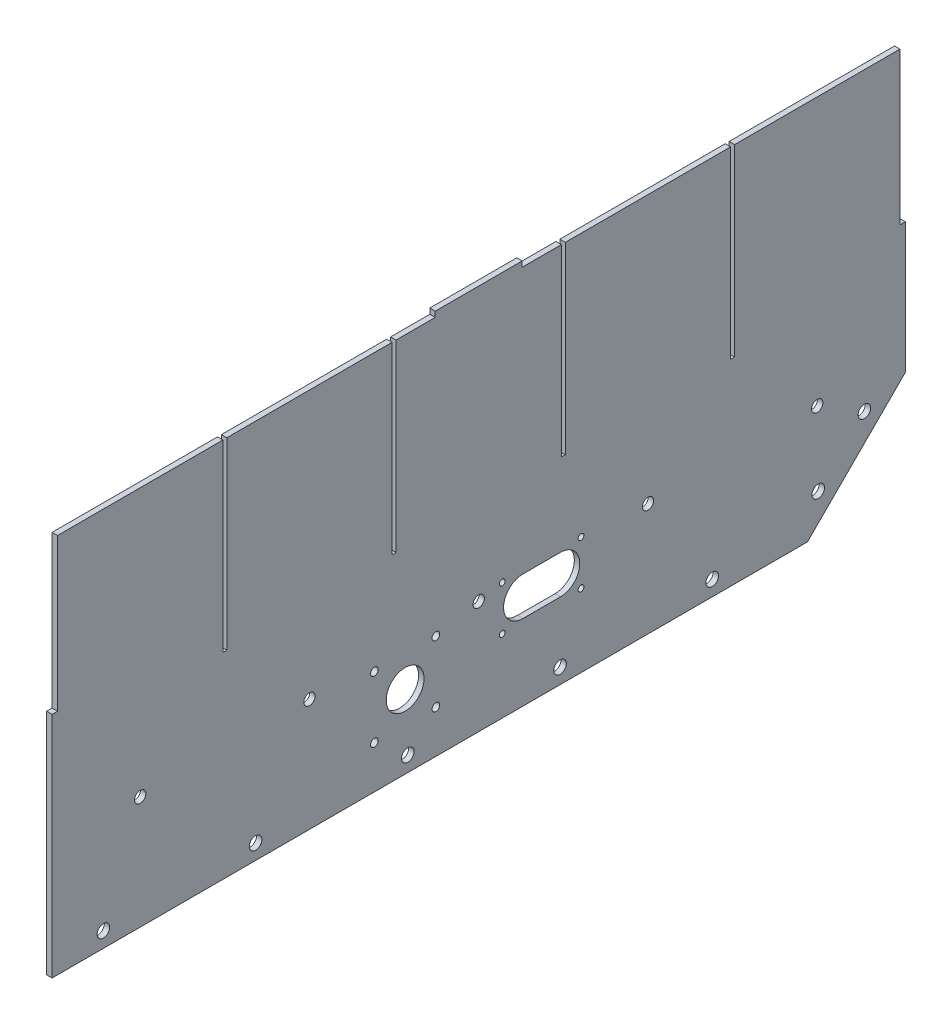
SolidWorks part; units mm, degrees
material "6061-T6 (SS)"
ref_plane "X-Y Datum" through (0, 0, 0) normal (0, 0, 1) x (1, 0, 0)
ref_plane "X-Z Datum" through (0, 0, 0) normal (0, 1, 0) x (1, 0, 0)
ref_plane "Y-Z Datum" through (0, 0, 0) normal (1, 0, 0) x (0, 0, -1)
sketch "Sketch1" plane through (0, 0, 0) normal (1, 0, 0) x (0, 0, -1)
  line L1 (-249.174, 82.55) -> (249.174, 82.55)
  line L2 (-249.174, 82.55) -> (-249.174, -82.55)
  line L3 (-249.174, -82.55) -> (249.174, -82.55)
  line L4 (249.174, 82.55) -> (249.174, -82.55)
  line L5 (-249.174, 82.55) -> (249.174, -82.55) construction
  line L6 (-249.174, -82.55) -> (249.174, 82.55) construction
  point P0 (0, 0)
  dimension "D1" = 165.1
  dimension "D2" = 498.348
extrude "Boss-Extrude1" add sketch "Sketch1" along normal mid plane 3.175
sketch "Sketch2" plane through (1.5875, 0, 0) normal (1, 0, 0) x (0, 0, -1)
  line L2 (249.174, -82.55) -> (192.024, -139.7)
  line L5 (-249.174, -82.55) -> (249.174, -82.55) construction
  line L6 (-249.174, -82.55) -> (249.174, -82.55)
  line L8 (192.024, -139.7) -> (-249.174, -139.7)
  line L9 (-249.174, -139.7) -> (-249.174, -82.55)
  line L11 (-249.174, 82.55) -> (-249.174, -82.55) construction
  line L12 (249.174, -82.55) -> (249.174, 82.55) construction
  dimension "D1" = 45
  dimension "D5" = 57.15
extrude "Boss-Extrude2" add sketch "Sketch2" against normal blind 3.175
sketch "Sketch3" plane through (-1.5875, 0, 0) normal (-1, 0, 0) x (0, 0, 1)
  line L0 (219.202, -139.7) -> (219.202, -130.81)
  line L1 (-192.024, -139.7) -> (249.174, -139.7) construction
  line L2 (219.202, -130.81) -> (249.174, -130.81)
  line L3 (249.174, 82.55) -> (249.174, -139.7) construction
  circle A0 centre (219.202, -130.81) radius 3.675
  dimension "D1" = 7.35
extrude "Cut-Extrude1" cut sketch "Sketch3" against normal through all contours L0 A0 L2 | L2 A0 L0
pattern_linear "LPattern1" count 5 spacing 88.9 along (0, 0, -1) of "Cut-Extrude1"
sketch "Sketch4" plane through (-1.5875, 0, 0) normal (-1, 0, 0) x (0, 0, 1)
  line L0 (-206.3924, -125.3316) -> (-198.3102, -117.2494)
  line L1 (-249.174, -82.55) -> (-192.024, -139.7) construction
  line L2 (-192.024, -139.7) -> (-183.9418, -131.6178)
  line L3 (-183.9418, -131.6178) -> (-198.3102, -117.2494)
  circle A0 centre (-198.3102, -117.2494) radius 3.675
extrude "Cut-Extrude2" cut sketch "Sketch4" against normal through all and the other way through all contours L3 A0 L0 | L0 A0 L3
pattern_linear "LPattern2" count 2 spacing 38.1 along (0, 0.7071, -0.7071) of "Cut-Extrude2"
sketch "Sketch5" plane through (1.5875, 0, 0) normal (1, 0, 0) x (0, 0, -1)
  line L1 (249.174, 82.55) -> (245.999, 82.55)
  line L2 (249.174, 82.55) -> (249.174, -6.35)
  line L3 (249.174, -6.35) -> (245.999, -6.35)
  line L4 (245.999, 82.55) -> (245.999, -6.35)
  line L5 (-249.174, 82.55) -> (-245.999, 82.55)
  line L6 (-249.174, 82.55) -> (-249.174, -6.35)
  line L7 (-249.174, -6.35) -> (-245.999, -6.35)
  line L8 (-245.999, 82.55) -> (-245.999, -6.35)
  dimension "D1" = 3.175
  dimension "D2" = 88.9
  dimension "D3" = 3.175
  dimension "D4" = 88.9
extrude "Cut-Extrude3" cut sketch "Sketch5" against normal through all
sketch "Sketch6" plane through (1.5875, 0, 0) normal (1, 0, 0) x (0, 0, -1)
  line L1 (149.4282, -24.892) -> (149.4282, 82.55) construction
  line L2 (122.174, 82.55) -> (249.174, 82.55)
  line L3 (149.4282, -24.892) -> (149.4282, 82.55)
  line L5 (149.4282, 82.55) -> (147.1422, 82.55)
  line L6 (149.4282, 82.55) -> (149.4282, -24.892)
  line L7 (149.4282, -24.892) -> (147.1422, -24.892)
  line L8 (147.1422, 82.55) -> (147.1422, -24.892)
  dimension "D1" = 2.286
  dimension "D2" = 107.442
extrude "Cut-Extrude4" cut sketch "Sketch6" against normal through all contours L2 L8 L7 L3
pattern_linear "LPattern3" count 4 spacing 98.8568 along (0, 0, 1) of "Cut-Extrude4"
sketch "Sketch8" plane through (1.5875, 0, 0) normal (1, 0, 0) x (0, 0, -1)
  line L0 (122.174, 85.725) -> (25.4, 85.725) construction
  line L1 (25.4, 82.55) -> (-25.4, 82.55)
  line L2 (25.4, 82.55) -> (25.4, 85.725)
  line L3 (25.4, 85.725) -> (-25.4, 85.725)
  line L4 (-25.4, 82.55) -> (-25.4, 85.725)
  line L5 (25.4, 82.55) -> (-25.4, 85.725) construction
  line L6 (25.4, 85.725) -> (-25.4, 82.55) construction
  point P0 (0, 84.1375)
  dimension "D1" = 3.175
  dimension "D2" = 50.8
extrude "Boss-Extrude3" add sketch "Sketch8" against normal blind 3.175
sketch "Sketch9" plane through (1.5875, 0, 0) normal (1, 0, 0) x (0, 0, -1)
  line L0 (-249.174, -6.35) -> (-249.174, -139.7) construction
  line L1 (192.024, -139.7) -> (-249.174, -139.7) construction
  circle A0 centre (-42.9768, -96.7994) radius 11.05
  dimension "D3" = 22.1
  dimension "D1" = 206.1972
  dimension "D2" = 42.9006
extrude "Cut-Extrude5" cut sketch "Sketch9" against normal through all
sketch "Sketch10" plane through (1.5875, 0, 0) normal (1, 0, 0) x (0, 0, -1)
  line L0 (192.024, -139.7) -> (-249.174, -139.7) construction
  circle A0 centre (0, -73.8124) radius 3
  dimension "D2" = 6
  dimension "D1" = 65.8876
hole_wizard "M6 Clearance Hole1" positions "Sketch11" profile "Sketch12" hole size "M6" standard "ANSI Metric" end condition through all
sketch "Sketch11" plane through (1.5875, 0, 0) normal (1, 0, 0) x (0, 0, -1)
  point P0 (0, -73.8124)
sketch "Sketch12" plane through (1.5875, -73.8124, 0) normal (0, 1, 0) x (0, 0, -1)
  line L0 (0, 0) -> (0, 3.175)
  line L1 (0, 3.175) -> (3.3, 3.175)
  line L2 (3.3, 3.175) -> (3.3, 0)
  line L5 (3.3, 0) -> (0, 0)
  line L11 (0, -6.35) -> (0, 107.95) construction
  dimension "Thru Hole Dia." = 6.6
  dimension "Thru Hole Depth" = 3.175
pattern_linear "LPattern4" count 3 spacing 98.8568 along (0, 0, 1) count 3 spacing 98.8568 along (0, 0, -1) of "M6 Clearance Hole1"
sketch "Sketch14" plane through (1.5875, 0, 0) normal (1, 0, 0) x (0, 0, -1)
  line L0 (192.024, -139.7) -> (-249.174, -139.7) construction
  line L1 (59.7662, -97.1042) -> (13.7662, -97.1042)
  line L2 (59.7662, -97.1042) -> (59.7662, -71.1042)
  line L3 (59.7662, -71.1042) -> (13.7662, -71.1042)
  line L4 (13.7662, -97.1042) -> (13.7662, -71.1042)
  line L5 (59.7662, -97.1042) -> (13.7662, -71.1042) construction
  line L6 (59.7662, -71.1042) -> (13.7662, -97.1042) construction
  line L7 (249.174, -82.55) -> (249.174, -6.35) construction
  line L8 (59.7662, -84.1042) -> (13.7662, -84.1042) construction
  line L9 (-25.0163, -114.7599) -> (-60.9373, -114.7599)
  line L10 (-25.0163, -114.7599) -> (-25.0163, -78.8389)
  line L11 (-25.0163, -78.8389) -> (-60.9373, -78.8389)
  line L12 (-60.9373, -114.7599) -> (-60.9373, -78.8389)
  line L13 (-25.0163, -114.7599) -> (-60.9373, -78.8389) construction
  line L14 (-25.0163, -78.8389) -> (-60.9373, -114.7599) construction
  line L15 (47.7662, -84.1042) -> (25.7662, -84.1042)
  line L16 (47.7662, -95.3542) -> (25.7662, -95.3542)
  line L17 (47.7662, -72.8542) -> (25.7662, -72.8542)
  arc A1 (47.7662, -95.3542) -> (47.7662, -72.8542) centre (47.7662, -84.1042) ccw
  arc A2 (25.7662, -72.8542) -> (25.7662, -95.3542) centre (25.7662, -84.1042) ccw
  point P0 (36.7662, -84.1042)
  point P10 (-42.9768, -96.7994)
  point P20 (36.7662, -84.1042)
  dimension "D7" = 11.25
  dimension "D1" = 46
  dimension "D2" = 26
  dimension "D3" = 42.5958
  dimension "D4" = 189.4078
  dimension "D5" = 35.921
  dimension "D6" = 22
hole_wizard "M4 Clearance Hole1" positions "Sketch17" profile "Sketch18" hole size "M4" standard "ANSI Metric" end condition through all
sketch "Sketch17" plane through (1.5875, 0, 0) normal (1, 0, 0) x (0, 0, -1)
  point P0 (-25.0163, -78.8389)
  point P3 (-60.9373, -78.8389)
  point P6 (-60.9373, -114.7599)
  point P9 (-25.0163, -114.7599)
sketch "Sketch18" plane through (1.5875, -78.8389, 25.0163) normal (0, 1, 0) x (0, 0, -1)
  line L0 (0, 0) -> (0, 3.175)
  line L1 (0, 3.175) -> (2.25, 3.175)
  line L2 (2.25, 3.175) -> (2.25, 0)
  line L5 (2.25, 0) -> (0, 0)
  line L11 (0, -6.35) -> (0, 107.95) construction
  dimension "Thru Hole Dia." = 4.5
  dimension "Thru Hole Depth" = 3.175
extrude "Cut-Extrude6" cut sketch "Sketch14" against normal through all
hole_wizard "M3 Clearance Hole1" positions "Sketch19" profile "Sketch20" hole size "M3" standard "ANSI Metric" end condition through all
sketch "Sketch19" plane through (1.5875, 0, 0) normal (1, 0, 0) x (0, 0, -1)
  point P0 (59.7662, -97.1042)
  point P3 (59.7662, -71.1042)
  point P6 (13.7662, -71.1042)
  point P9 (13.7662, -97.1042)
sketch "Sketch20" plane through (1.5875, -97.1042, -59.7662) normal (0, 1, 0) x (0, 0, -1)
  line L0 (0, 0) -> (0, 3.175)
  line L1 (0, 3.175) -> (1.7, 3.175)
  line L2 (1.7, 3.175) -> (1.7, 0)
  line L5 (1.7, 0) -> (0, 0)
  line L11 (0, -6.35) -> (0, 107.95) construction
  dimension "Thru Hole Dia." = 3.4
  dimension "Thru Hole Depth" = 3.175
